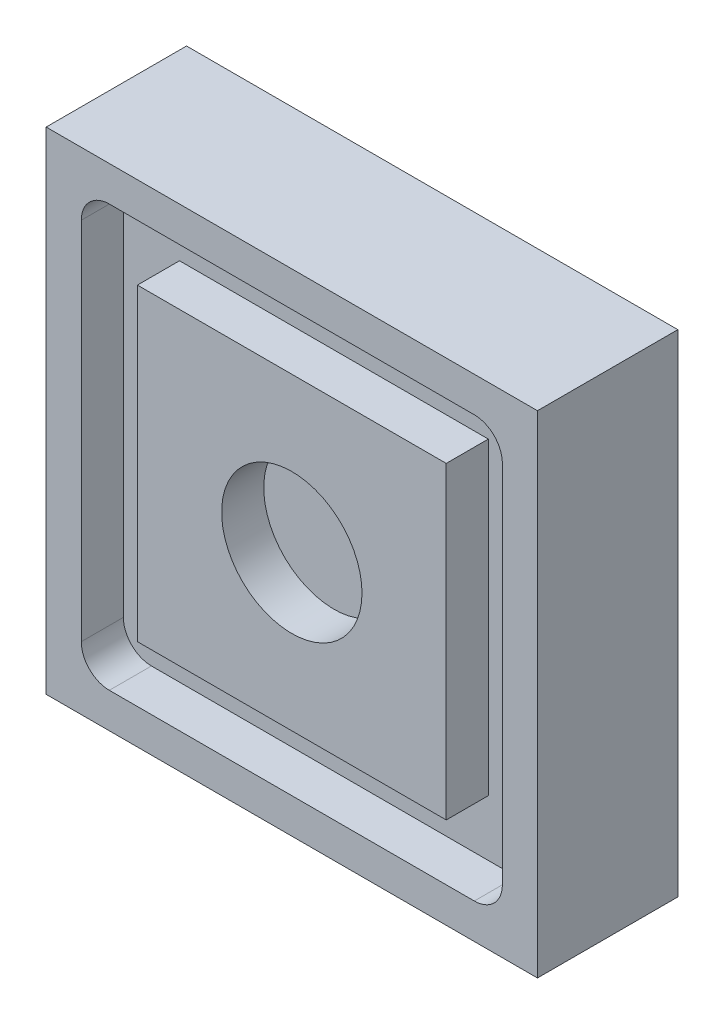
SolidWorks part; units mm, degrees
material "Hêtre"
ref_plane "Plan de face" through (0, 0, 0) normal (0, 0, 1) x (1, 0, 0)
ref_plane "Plan de dessus" through (0, 0, 0) normal (0, 1, 0) x (1, 0, 0)
ref_plane "Plan de droite" through (0, 0, 0) normal (1, 0, 0) x (0, 0, -1)
sketch "Esquisse2" plane through (0, 0, 0) normal (0, 0, 1) x (1, 0, 0)
  line L1 (17.5, -17.5) -> (-17.5, -17.5)
  line L2 (17.5, -17.5) -> (17.5, 17.5)
  line L3 (17.5, 17.5) -> (-17.5, 17.5)
  line L4 (-17.5, -17.5) -> (-17.5, 17.5)
  line L5 (17.5, -17.5) -> (-17.5, 17.5) construction
  line L6 (17.5, 17.5) -> (-17.5, -17.5) construction
  point P0 (0, 0)
  dimension "D1" = 35
  dimension "D2" = 35
extrude "Boss.-Extru.2" add sketch "Esquisse2" along normal blind 10
sketch "Esquisse3" plane through (0, 0, 10) normal (0, 0, 1) x (1, 0, 0)
  line L1 (13, -15) -> (-13, -15)
  line L2 (15, -13) -> (15, 13)
  line L3 (13, 15) -> (-13, 15)
  line L4 (-15, -13) -> (-15, 13)
  line L5 (15, -15) -> (-15, 15) construction
  line L6 (15, 15) -> (-15, -15) construction
  arc A0 (-13, -15) -> (-15, -13) centre (-13, -13) cw
  arc A1 (13, -15) -> (15, -13) centre (13, -13) ccw
  arc A2 (15, 13) -> (13, 15) centre (13, 13) ccw
  arc A3 (-13, 15) -> (-15, 13) centre (-13, 13) ccw
  point P0 (0, 0)
  dimension "D3" = 2
  dimension "D1" = 30
  dimension "D2" = 30
extrude "Enlèv. de mat.-Extru.-Mince1" cut sketch "Esquisse3" against normal blind 3 thin
sketch "Esquisse4" plane through (0, 0, 10) normal (0, 0, 1) x (1, 0, 0)
  circle A0 centre (0, 0) radius 5
  dimension "D1" = 10
extrude "Enlèv. mat.-Extru.1" cut sketch "Esquisse4" against normal blind 3
